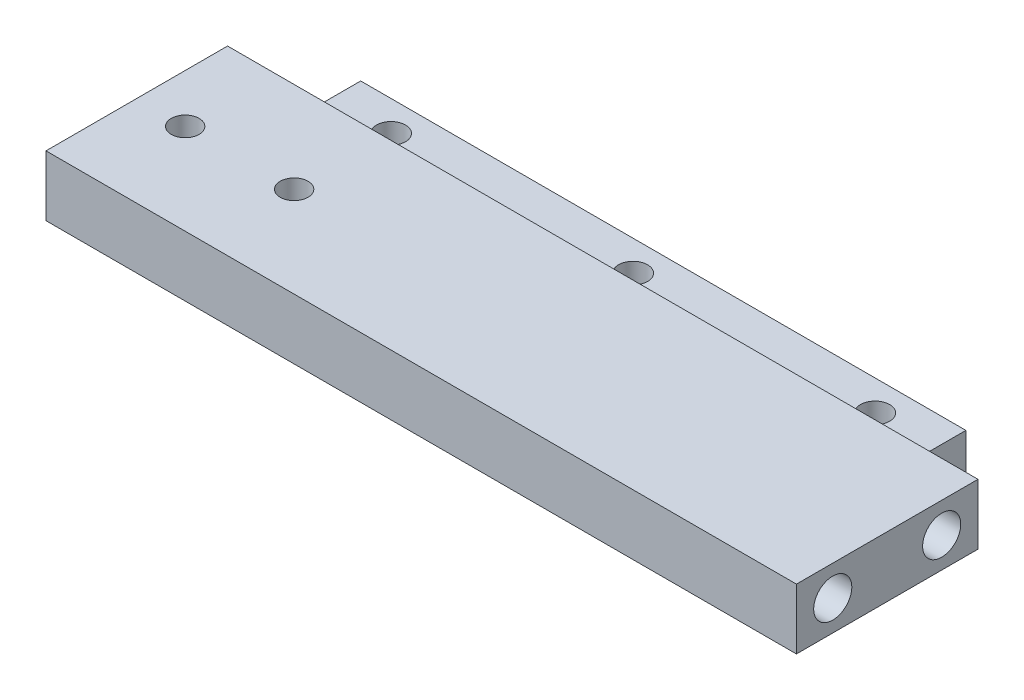
SolidWorks part; units mm, degrees
ref_plane "Plano frontal" through (0, 0, 0) normal (0, 0, 1) x (1, 0, 0)
ref_plane "Plano superior" through (0, 0, 0) normal (0, 1, 0) x (1, 0, 0)
ref_plane "Plano direito" through (0, 0, 0) normal (1, 0, 0) x (0, 0, -1)
sketch "Esboço1" plane through (0, 0, 0) normal (0, 1, 0) x (1, 0, 0)
  line L1 (0, 0) -> (62, 0)
  line L2 (0, 0) -> (0, 15)
  line L3 (0, 15) -> (62, 15)
  line L4 (62, 0) -> (62, 15)
  dimension "D1" = 62
  dimension "D2" = 15
extrude "Ressalto-extrusão1" add sketch "Esboço1" along normal blind 5
hole_wizard "Furo roscado para conduíte de M3x0.51" positions "Esboço2" profile "Esboço4" tap size "M3x0.5" standard "Helicoil® Metric"
sketch "Esboço2" plane through (0, 0, 0) normal (-1, 0, 0) x (0, 0, 1)
  line L1 (-15, 2.5) -> (0, 2.5) construction
  line L2 (-15, 5) -> (-15, 0) construction
  line L3 (0, 5) -> (0, 0) construction
  point P0 (-12, 2.5)
  point P2 (-3, 2.5)
  dimension "D1" = 3
  dimension "D2" = 3
sketch "Esboço4" plane through (0, 2.5, -12) normal (0, 1, 0) x (0, 0, 1)
  line L0 (0, 0) -> (0, 10.9464)
  line L1 (0, 10.9464) -> (1.575, 10)
  line L2 (1.575, 10) -> (1.575, 0)
  line L5 (1.575, 0) -> (0, 0)
  line L10 (0, 10.9464) -> (-1.575, 10) construction
  line L11 (0, -6.35) -> (0, 107.95) construction
  dimension "Tap Drill Dia." = 3.15
  dimension "Tap Drill Depth" = 10
  dimension "Drill Angle" = 118
cosmetic thread "Rosca de furo1" parameters "D1"=10, "D2"=3.716
cosmetic thread "Rosca de furo2" parameters "D1"=10, "D2"=3.716
hole_wizard "Furo roscado para conduíte de M3x0.52" positions "Esboço8" profile "Esboço6" tap size "M3x0.5" standard "Helicoil® Metric"
sketch "Esboço8" plane through (62, 0, 0) normal (1, 0, 0) x (0, 0, -1)
  line L0 (0, 2.5) -> (15, 2.5) construction
  line L1 (0, 5) -> (0, 0) construction
  line L2 (15, 5) -> (15, 0) construction
  point P0 (3, 2.5)
  point P2 (12, 2.5)
  dimension "D1" = 3
  dimension "D2" = 3
sketch "Esboço6" plane through (62, 2.5, -3) normal (0, 1, 0) x (0, 0, -1)
  line L0 (0, 0) -> (0, 8.4464)
  line L1 (0, 8.4464) -> (1.575, 7.5)
  line L2 (1.575, 7.5) -> (1.575, 0)
  line L5 (1.575, 0) -> (0, 0)
  line L10 (0, 8.4464) -> (-1.575, 7.5) construction
  line L11 (0, -6.35) -> (0, 107.95) construction
  dimension "Tap Drill Dia." = 3.15
  dimension "Tap Drill Depth" = 7.5
  dimension "Drill Angle" = 118
cosmetic thread "Rosca de furo3" parameters "D1"=10, "D2"=3.716
cosmetic thread "Rosca de furo4" parameters "D1"=10, "D2"=3.716
hole_wizard "Furo roscado para conduíte de M2.2x0.451" positions "Esboço9" profile "Esboço11" tap size "M2.2x0.45" standard "Helicoil® Metric" end condition through all
sketch "Esboço9" plane through (0, 0, 0) normal (0, -1, 0) x (-1, 0, 0)
  line L0 (-62, 7.5) -> (0, 7.5) construction
  line L1 (0, 15) -> (0, 0) construction
  line L3 (-62, 0) -> (-62, 15) construction
  point P0 (-4, 7.5)
  point P2 (-13, 7.5)
  dimension "D1" = 4
  dimension "D2" = 13
sketch "Esboço11" plane through (4, 0, -7.5) normal (1, 0, 0) x (0, 0, -1)
  line L0 (0, 0) -> (0, 5)
  line L1 (0, 5) -> (1.15, 5)
  line L2 (1.15, 5) -> (1.15, 0)
  line L5 (1.15, 0) -> (0, 0)
  line L11 (0, -6.35) -> (0, 107.95) construction
  dimension "Thru Tap Drill Dia." = 2.3
  dimension "Thru Tap Drill Depth" = 5
cosmetic thread "Rosca de furo5" parameters "D1"=10, "D2"=2.845
cosmetic thread "Rosca de furo6" parameters "D1"=10, "D2"=2.845
sketch "Esboço12" plane through (0, 0, -15) normal (0, 0, -1) x (-1, 0, 0)
  line L0 (-31, 5) -> (-31, 0) construction
  line L1 (-62, 5) -> (0, 5) construction
  line L2 (-62, 0) -> (0, 0) construction
  line L4 (-56, 3) -> (-6, 3)
  line L5 (-56, 3) -> (-56, 0)
  line L6 (-56, 0) -> (-6, 0)
  line L7 (-6, 3) -> (-6, 0)
  line L8 (-56, 3) -> (-6, 0) construction
  line L9 (-56, 0) -> (-6, 3) construction
  point P6 (-31, 1.5)
  dimension "D1" = 3
  dimension "D2" = 50
extrude "Ressalto-extrusão2" add sketch "Esboço12" along normal blind 5
hole_wizard "Escareado para parafuso de máquina com cabeça chata de M21" positions "Esboço13" profile "Esboço14" countersink size "M2" standard "Ansi Metric" end condition through all
sketch "Esboço13" plane through (0, 0, 0) normal (0, -1, 0) x (-1, 0, 0)
  line L0 (-31, 20) -> (-31, 0) construction
  line L1 (-56, 20) -> (-6, 20) construction
  line L2 (0, 0) -> (-62, 0) construction
  point P18 (-51, 17.5)
  point P22 (-31, 17.5)
  point P29 (-11, 17.5)
  point P31 (0, 0)
  point P32 (0, 0)
  dimension "D1" = 2.5
  dimension "D3" = 20
sketch "Esboço14" plane through (11, 0, -17.5) normal (1, 0, 0) x (0, 0, -1)
  line L0 (0, 0) -> (0, 5)
  line L1 (0, 5) -> (1.2, 5)
  line L2 (1.2, 5) -> (1.2, 1)
  line L3 (1.2, 1) -> (2.2, 0)
  line L5 (2.2, 0) -> (0, 0)
  line L6 (-1.2, 1) -> (-2.2, 0) construction
  line L11 (0, -6.35) -> (0, 107.95) construction
  dimension "Thru Hole Dia." = 2.4
  dimension "Thru Hole Depth" = 5
  dimension "Near C'Sink Dia." = 4.4
  dimension "Near C'Sink Angle" = 90
